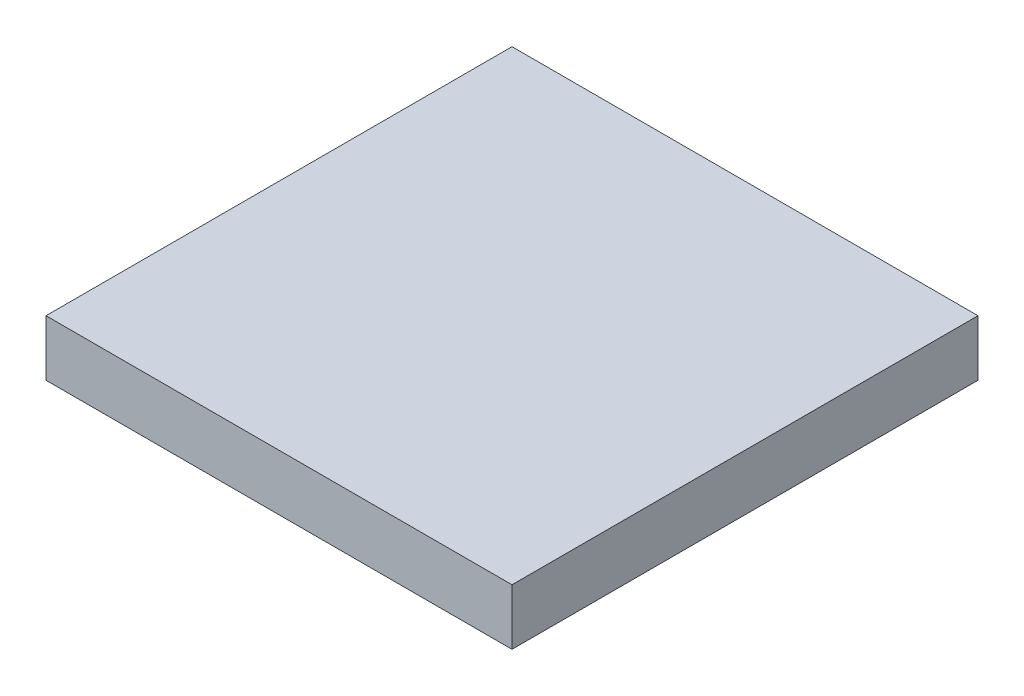
SolidWorks part; units mm, degrees
ref_plane "Front Plane" through (0, 0, 0) normal (0, 0, 1) x (1, 0, 0)
ref_plane "Top Plane" through (0, 0, 0) normal (0, 1, 0) x (1, 0, 0)
ref_plane "Right Plane" through (0, 0, 0) normal (1, 0, 0) x (0, 0, -1)
sketch "Sketch1" plane through (0, 0, 0) normal (0, 1, 0) x (1, 0, 0)
  line L1 (0, 0) -> (50, 0)
  line L2 (0, 0) -> (0, 50)
  line L3 (0, 50) -> (50, 50)
  line L4 (50, 0) -> (50, 50)
  dimension "D1" = 50
extrude "Boss-Extrude2" add sketch "Sketch1" along normal blind 6
sketch "Sketch3" plane through (0, 6, 0) normal (0, 1, 0) x (1, 0, 0)
  line L0 (0, 0) -> (50, 50) construction
  line L1 (0, 50) -> (50, 0) construction
